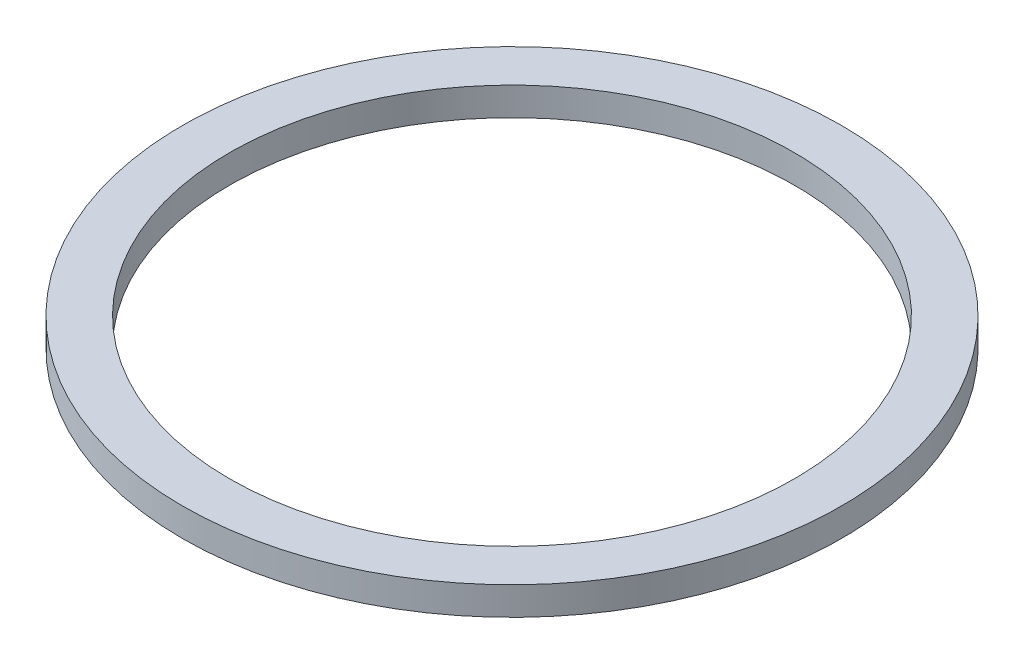
SolidWorks part; units mm, degrees
ref_plane "Front Plane" through (0, 0, 0) normal (0, 0, 1) x (1, 0, 0)
ref_plane "Top Plane" through (0, 0, 0) normal (0, 1, 0) x (1, 0, 0)
ref_plane "Right Plane" through (0, 0, 0) normal (1, 0, 0) x (0, 0, -1)
sketch "Sketch1" plane through (0, 0, 0) normal (0, 1, 0) x (1, 0, 0)
  circle A0 centre (0, 0) radius 350
  circle A1 centre (0, 0) radius 300
  dimension "D1" = 600
  dimension "D2" = 700
extrude "Boss-Extrude1" add sketch "Sketch1" along normal blind 30
